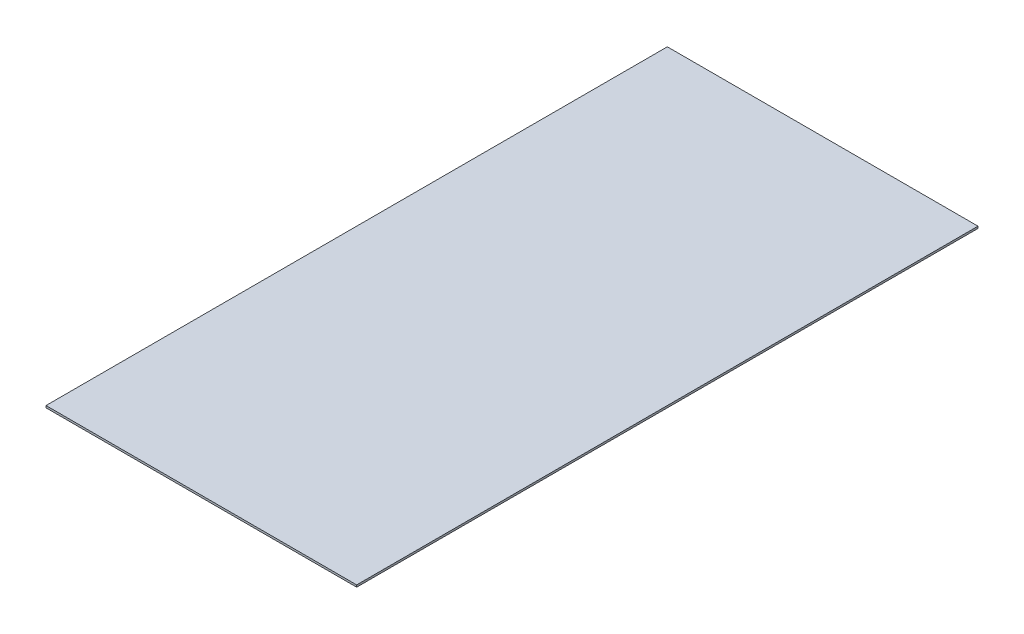
SolidWorks part; units mm, degrees
material "ASTM A36 Acero"
ref_plane "Alzado" through (0, 0, 0) normal (0, 0, 1) x (1, 0, 0)
ref_plane "Planta" through (0, 0, 0) normal (0, 1, 0) x (1, 0, 0)
ref_plane "Vista lateral" through (0, 0, 0) normal (1, 0, 0) x (0, 0, -1)
sketch "Croquis1" plane through (0, 0, 0) normal (0, 1, 0) x (1, 0, 0)
  line L1 (-609.6, -1219.2) -> (609.6, -1219.2)
  line L2 (-609.6, -1219.2) -> (-609.6, 1219.2)
  line L3 (-609.6, 1219.2) -> (609.6, 1219.2)
  line L4 (609.6, -1219.2) -> (609.6, 1219.2)
  line L5 (-609.6, -1219.2) -> (609.6, 1219.2) construction
  line L6 (-609.6, 1219.2) -> (609.6, -1219.2) construction
  point P0 (0, 0)
  dimension "D1" = 2438.4
  dimension "D2" = 1219.2
extrude "Saliente-Extruir1" add sketch "Croquis1" along normal blind 7.9
